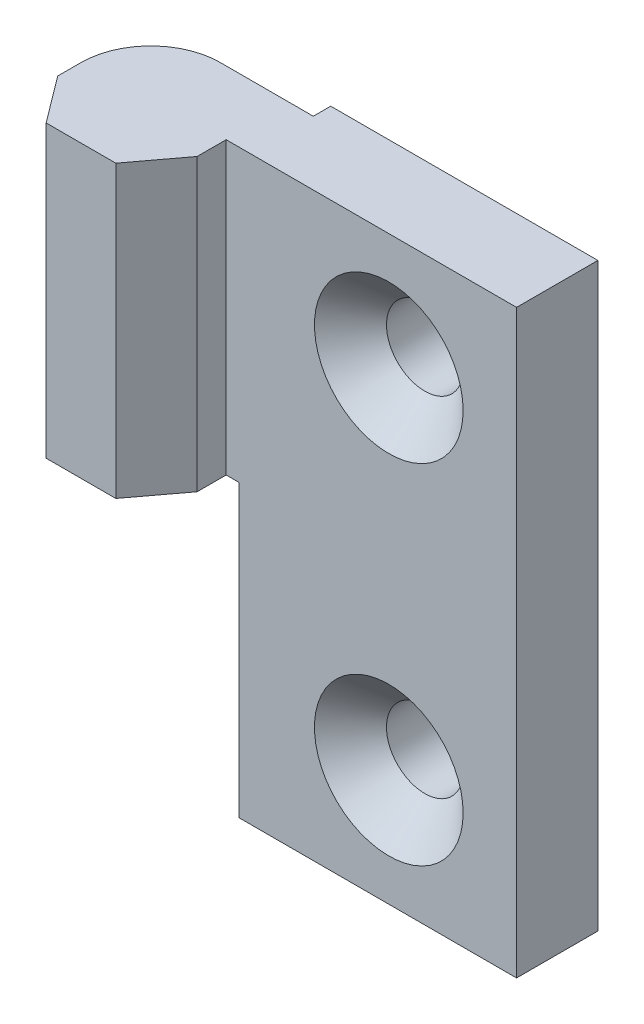
SolidWorks part; units mm, degrees
ref_plane "前视基准面" through (0, 0, 0) normal (0, 0, 1) x (1, 0, 0)
ref_plane "上视基准面" through (0, 0, 0) normal (0, 1, 0) x (1, 0, 0)
ref_plane "右视基准面" through (0, 0, 0) normal (1, 0, 0) x (0, 0, -1)
sketch "草图1" plane through (0, 0, 0) normal (0, 1, 0) x (1, 0, 0)
  line L0 (0, 0) -> (-25, 0)
  line L1 (-25, 0) -> (-25, -2.5)
  line L2 (-25, -2.5) -> (-28, -6.5)
  line L3 (-28, -6.5) -> (-34, -6.5)
  line L4 (-34, -6.5) -> (-37, -2.5)
  line L5 (-37, -2.5) -> (-37, 5.5)
  line L6 (-37, 5.5) -> (-23, 5.5)
  line L7 (-23, 5.5) -> (-23, 7)
  line L8 (-23, 7) -> (0, 7)
  line L9 (0, 7) -> (0, 0)
  line L10 (-31, -6.5) -> (-31, 1.1679) construction
  dimension "D1" = 7
  dimension "D2" = 25
  dimension "D3" = 4
  dimension "D4" = 6
  dimension "D5" = 5.5
  dimension "D6" = 23
  dimension "D7" = 37
  dimension "D8" = 12
extrude "凸台-拉伸1" add sketch "草图1" along normal blind 50
fillet "圆角1" radius 6 1 edges at (-37, 25, -5.5)
sketch "草图2" plane through (0, 0, 6.5) normal (0, 0, 1) x (1, 0, 0)
  line L0 (-25, 50) -> (-25, 0) construction
  line L1 (-37, 0) -> (-25, 0)
  line L2 (-37, 0) -> (-37, 25)
  line L3 (-37, 25) -> (-25, 25)
  line L4 (-25, 0) -> (-25, 25)
  line L5 (-34, 50) -> (-28, 50) construction
  dimension "D1" = 25
hole_wizard "打孔尺寸根据内六角花形半沉头螺钉的类型1" positions "草图4" profile "草图3" countersink size "M6" standard "GB" end condition through all
sketch "草图4" plane through (0, 0, 0) normal (0, 0, 1) x (1, 0, 0)
  line L0 (0, 25) -> (-21.0906, 25) construction
  line L1 (0, 50) -> (0, 0) construction
  point P0 (-11, 40)
  point P1 (-11, 10)
  dimension "D1" = 30
  dimension "D2" = 20
sketch "草图3" plane through (-11, 40, 0) normal (1, 0, 0) x (0, -1, 0)
  line L0 (0, 0) -> (0, 7)
  line L1 (0, 7) -> (3.3, 7)
  line L2 (3.3, 7) -> (3.3, 3.1)
  line L3 (3.3, 3.1) -> (6.4, 0)
  line L5 (6.4, 0) -> (0, 0)
  line L6 (-3.3, 3.1) -> (-6.4, 0) construction
  line L11 (0, -6.35) -> (0, 107.95) construction
  dimension "通孔孔直径" = 6.6
  dimension "通孔孔深度" = 7
  dimension "近端锥形沉头孔直径" = 12.8
  dimension "近端锥形沉头孔角度" = 90
sketch "草图5" plane through (0, 0, -5.5) normal (0, 0, -1) x (-1, 0, 0)
  line L1 (37, 25) -> (23, 25)
  line L2 (37, 25) -> (37, 0)
  line L3 (37, 0) -> (23, 0)
  line L4 (23, 25) -> (23, 0)
loft "切除-放样1" cut profiles "草图2", "草图5"
